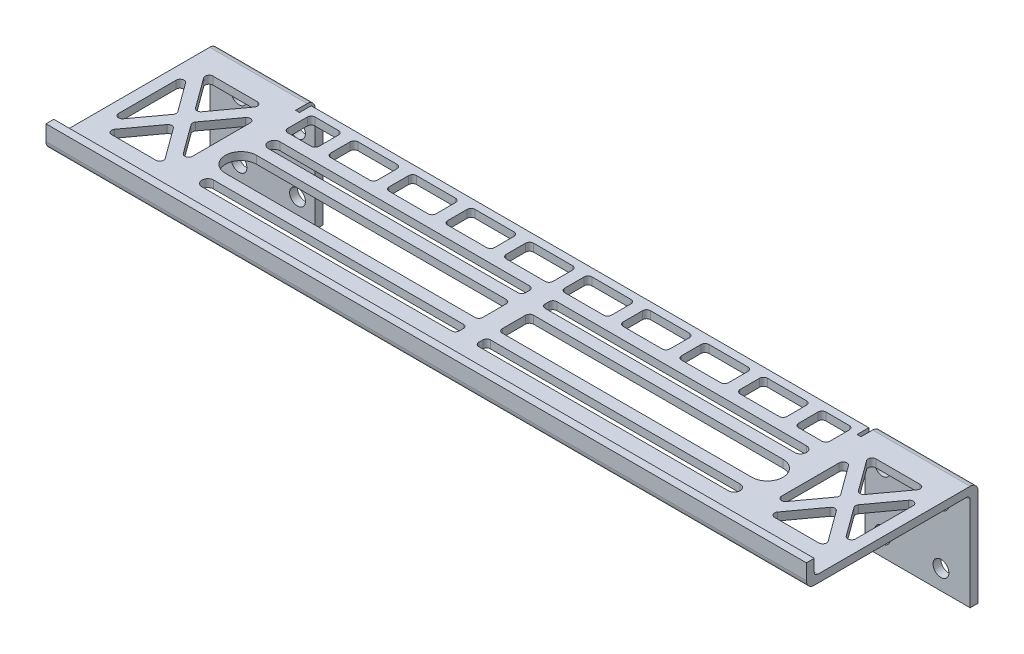
SolidWorks part; units mm, degrees
material "AISI 304"
ref_plane "Front Plane" through (0, 0, 0) normal (0, 0, 1) x (1, 0, 0)
ref_plane "Top Plane" through (0, 0, 0) normal (0, 1, 0) x (1, 0, 0)
ref_plane "Right Plane" through (0, 0, 0) normal (1, 0, 0) x (0, 0, -1)
sketch "Sketch1" plane through (0, 0, 0) normal (0, 1, 0) x (1, 0, 0)
  line L1 (-97.5, 17.5) -> (97.5, 17.5)
  line L2 (-97.5, 17.5) -> (-97.5, -17.5)
  line L3 (-97.5, -17.5) -> (97.5, -17.5)
  line L4 (97.5, 17.5) -> (97.5, -17.5)
  line L5 (-97.5, 17.5) -> (97.5, -17.5) construction
  line L6 (-97.5, -17.5) -> (97.5, 17.5) construction
  point P0 (0, 0)
  dimension "D1" = 195
  dimension "D2" = 35
extrude "Boss-Extrude1" add sketch "Sketch1" along normal blind 2
sketch "Sketch2" plane through (0, 0, -17.5) normal (0, 0, -1) x (-1, 0, 0)
  line L0 (-97.5, 2) -> (-97.5, -25)
  line L1 (-97.5, -25) -> (-72.5, -25)
  line L2 (-72.5, -25) -> (-72.5, 2)
  line L3 (-97.5, 2) -> (97.5, 2) construction
  line L4 (-72.5, 2) -> (-97.5, 2)
  line L5 (0, 22.3225) -> (0, -25) construction
  line L6 (72.5, -25) -> (72.5, 2)
  line L7 (97.5, -25) -> (72.5, -25)
  line L8 (97.5, 2) -> (97.5, -25)
  line L9 (72.5, 2) -> (97.5, 2)
  dimension "D1" = 25
  dimension "D2" = 27
extrude "Boss-Extrude2" add sketch "Sketch2" along normal blind 2
fillet "Fillet1" radius 2 2 edges at (-85, 2, -19.5) (85, 2, -19.5)
fillet "Fillet2" radius 1 2 edges at (85, 0, -17.5) (-85, 0, -17.5)
sketch "Sketch3" plane through (0, 2, 0) normal (0, 1, 0) x (1, 0, 0)
  line L0 (-72.5, 17.5) -> (-72.5, 14.5)
  line L1 (-72.5, 14.5) -> (-71.5, 14.5)
  line L2 (-71.5, 14.5) -> (-71.5, 17.5)
  line L3 (72.5, 17.5) -> (-72.5, 17.5) construction
  line L4 (-71.5, 17.5) -> (-72.5, 17.5)
  line L5 (0, 27.242) -> (0, -22.4777) construction
  line L6 (71.5, 14.5) -> (71.5, 17.5)
  line L7 (72.5, 14.5) -> (71.5, 14.5)
  line L8 (72.5, 17.5) -> (72.5, 14.5)
  line L9 (71.5, 17.5) -> (72.5, 17.5)
  dimension "D1" = 1
  dimension "D2" = 3
extrude "Cut-Extrude1" cut sketch "Sketch3" against normal through all
sketch "Sketch4" plane through (0, 2, 0) normal (0, 1, 0) x (1, 0, 0)
  line L1 (-97.5, 17.5) -> (-97.5, -17.5) construction
  line L2 (97.5, -17.5) -> (97.5, 17.5) construction
  line L3 (-67.5, -4.5) -> (67.5, -4.5) construction
  line L4 (-67.5, -0.5) -> (67.5, -0.5)
  line L5 (-67.5, -8.5) -> (67.5, -8.5)
  line L6 (-97.5, -13) -> (97.5, -13) construction
  line L7 (-97.5, 4) -> (97.5, 4) construction
  line L8 (-67.5, 4) -> (67.5, 4) construction
  line L9 (-67.5, 5.5025) -> (67.5, 5.5025)
  line L10 (-67.5, 2.4975) -> (67.5, 2.4975)
  line L11 (67.5, -4.5) -> (67.5, 13.2752) construction
  line L12 (-67.5, -4.5) -> (-67.5, 15.5373) construction
  line L13 (-67.5, -13) -> (67.5, -13) construction
  line L14 (-67.5, -14.5025) -> (67.5, -14.5025)
  line L15 (-67.5, -11.4975) -> (67.5, -11.4975)
  line L16 (71.5, 17.5) -> (-71.5, 17.5) construction
  line L17 (67.5, -4.5) -> (67.5, -23.9923) construction
  line L18 (-67.5, -4.5) -> (-67.5, -26.609) construction
  arc A0 (-67.5, -0.5) -> (-67.5, -8.5) centre (-67.5, -4.5) ccw
  arc A1 (67.5, -8.5) -> (67.5, -0.5) centre (67.5, -4.5) ccw
  arc A2 (-67.5, 5.5025) -> (-67.5, 2.4975) centre (-67.5, 4) ccw
  arc A3 (67.5, 2.4975) -> (67.5, 5.5025) centre (67.5, 4) ccw
  arc A4 (-67.5, -14.5025) -> (-67.5, -11.4975) centre (-67.5, -13) cw
  arc A5 (67.5, -11.4975) -> (67.5, -14.5025) centre (67.5, -13) cw
  point P8 (0, -4.5)
  point P19 (0, 4)
  point P26 (-67.5, -10)
  point P31 (0, -13)
  dimension "D1" = 4
  dimension "D6" = 1.5025
  dimension "D8" = 1.5025
  dimension "D2" = 30
  dimension "D3" = 30
  dimension "D5" = 8.5
  dimension "D4" = 8.5
  dimension "D7" = 22
extrude "Cut-Extrude2" cut sketch "Sketch4" against normal through all
sketch "Sketch6" plane through (0, 2, 0) normal (0, 1, 0) x (1, 0, 0)
  line L0 (0, 24.7593) -> (0, -32.236) construction
  line L1 (-75.5, 8.9577) -> (-75.5, -11.9577)
  line L2 (-72.5, 14.5) -> (-97.5, 14.5) construction
  line L3 (-72.5, 14.5) -> (-72.5, -17.5) construction
  line L4 (-72.5, -17.5) -> (-97.5, -17.5) construction
  line L5 (-97.5, 14.5) -> (-97.5, -17.5) construction
  line L6 (-77.3578, -14.5) -> (-92.6422, -14.5)
  line L7 (-94.5, 8.9577) -> (-94.5, -11.9577)
  line L8 (-77.3578, 11.5) -> (-92.6422, 11.5)
  line L9 (-94.5, 11.5) -> (-75.5, -14.5) construction
  line L10 (-75.5, 11.5) -> (-94.5, -14.5) construction
  line L11 (-94.5, 8.9577) -> (-86.8578, -1.5)
  line L12 (-77.3578, 11.5) -> (-85, 1.0423)
  line L13 (-92.6422, 11.5) -> (-85, 1.0423)
  line L14 (-75.5, 8.9577) -> (-83.1422, -1.5)
  line L15 (-86.8578, -1.5) -> (-94.5, -11.9577)
  line L16 (-93.2889, 12.385) -> (-74.2889, -13.615) construction
  line L17 (-95.7111, 10.615) -> (-76.7111, -15.385) construction
  line L18 (-76.7111, 12.385) -> (-95.7111, -13.615) construction
  line L19 (-74.2889, 10.615) -> (-93.2889, -15.385) construction
  line L20 (-94.5, 11.5) -> (-94.5, -14.5) construction
  line L21 (-75.5, 11.5) -> (-94.5, 11.5) construction
  line L22 (-75.5, 11.5) -> (-75.5, -14.5) construction
  line L23 (-75.5, -14.5) -> (-94.5, -14.5) construction
  line L24 (-85, -4.0423) -> (-77.3578, -14.5)
  line L25 (-85, -4.0423) -> (-92.6422, -14.5)
  line L26 (-83.1422, -1.5) -> (-75.5, -11.9577)
  line L27 (75.5, 11.5) -> (94.5, -14.5) construction
  line L28 (94.5, 11.5) -> (75.5, -14.5) construction
  line L29 (97.5, 14.5) -> (97.5, -17.5) construction
  line L30 (72.5, -17.5) -> (97.5, -17.5) construction
  line L31 (72.5, 14.5) -> (72.5, -17.5) construction
  line L32 (72.5, 14.5) -> (97.5, 14.5) construction
  line L33 (83.1422, -1.5) -> (75.5, -11.9577)
  line L34 (85, -4.0423) -> (92.6422, -14.5)
  line L35 (85, -4.0423) -> (77.3578, -14.5)
  line L36 (86.8578, -1.5) -> (94.5, -11.9577)
  line L37 (75.5, 8.9577) -> (83.1422, -1.5)
  line L38 (92.6422, 11.5) -> (85, 1.0423)
  line L39 (77.3578, 11.5) -> (85, 1.0423)
  line L40 (94.5, 8.9577) -> (86.8578, -1.5)
  line L41 (77.3578, 11.5) -> (92.6422, 11.5)
  line L42 (94.5, 8.9577) -> (94.5, -11.9577)
  line L43 (77.3578, -14.5) -> (92.6422, -14.5)
  line L44 (75.5, 8.9577) -> (75.5, -11.9577)
  dimension "D1" = 3
  dimension "D2" = 1.5
  dimension "D3" = 1.5
extrude "Cut-Extrude4" cut sketch "Sketch6" against normal through all
fillet "Fillet3" radius 1 24 edges at (92.6422, 1, 14.5) (77.3578, 1, 14.5) (75.5, 1, 11.9577) (94.5, 1, 11.9577) (85, 1, 4.0423) (75.5, 1, -8.9577) (94.5, 1, -8.9577) (92.6422, 1, -11.5) (77.3578, 1, -11.5) (86.8578, 1, 1.5) (83.1422, 1, 1.5) (85, 1, -1.0423) (-92.6422, 1, -11.5) (-85, 1, -1.0423) (-77.3578, 1, -11.5) (-75.5, 1, -8.9577) (-75.5, 1, 11.9577) (-77.3578, 1, 14.5) (-85, 1, 4.0423) (-83.1422, 1, 1.5) (-92.6422, 1, 14.5) (-94.5, 1, 11.9577) (-86.8578, 1, 1.5) (-94.5, 1, -8.9577)
sketch "Sketch7" plane through (0, 0, -19.5) normal (0, 0, -1) x (-1, 0, 0)
  line L0 (0, 25.9328) -> (0, -38.6438) construction
  line L1 (-97.5, -12.5) -> (97.5, -12.5) construction
  line L2 (-97.5, 0) -> (-97.5, -25) construction
  line L3 (97.5, -25) -> (97.5, 0) construction
  line L4 (-97.5, -20) -> (97.5, -20) construction
  line L5 (-97.5, -5) -> (97.5, -5) construction
  circle A0 centre (-90, -5) radius 2.025
  circle A1 centre (-75, -5) radius 2.025
  circle A2 centre (-75, -20) radius 2.025
  circle A3 centre (-90, -20) radius 2.025
  circle A4 centre (90, -20) radius 2.025
  circle A5 centre (75, -20) radius 2.025
  circle A6 centre (75, -5) radius 2.025
  circle A7 centre (90, -5) radius 2.025
  dimension "D3" = 4.05
  dimension "D4" = 90
  dimension "D7" = 15
  dimension "D8" = 15
  dimension "D1" = 7.5
  dimension "D2" = 7.5
  dimension "D5" = 2
  dimension "D6" = 2
extrude "Cut-Extrude5" cut sketch "Sketch7" against normal through all
sketch "Sketch8" plane through (0, 0, -19.5) normal (0, 0, -1) x (-1, 0, 0)
  line L0 (-72.5, -2) -> (-70.5, -2)
  line L1 (-72.5, -25) -> (-72.5, 0) construction
  line L2 (-70.5, -2) -> (-70.5, -25)
  line L3 (-70.5, -25) -> (-72.5, -25)
  line L4 (-72.5, -25) -> (-72.5, -2)
  line L5 (-97.5, -25) -> (-72.5, -25) construction
  line L6 (-71.5, 0) -> (71.5, 0) construction
  line L7 (0, 16.8942) -> (0, -14.9488) construction
  line L8 (70.5, -25) -> (72.5, -25)
  line L9 (70.5, -2) -> (70.5, -25)
  line L10 (72.5, -2) -> (70.5, -2)
  line L11 (72.5, -25) -> (72.5, -2)
  dimension "D1" = 2
  dimension "D2" = 2
extrude "Boss-Extrude3" add sketch "Sketch8" against normal blind 2
sketch "Sketch10" plane through (0, 2, 0) normal (0, 1, 0) x (1, 0, 0)
  line L0 (-97.5, -17.5) -> (-97.5, -22.5)
  line L1 (-97.5, -22.5) -> (97.5, -22.5)
  line L2 (97.5, -22.5) -> (97.5, -17.5)
  line L3 (97.5, -17.5) -> (-97.5, -17.5)
  dimension "D1" = 5
extrude "Boss-Extrude5" add sketch "Sketch10" against normal blind 2
sketch "Sketch11" plane through (0, 0, 22.5) normal (0, 0, 1) x (1, 0, 0)
  line L0 (97.5, 0) -> (-97.5, 0)
  line L1 (-97.5, 0) -> (-97.5, 6)
  line L2 (-97.5, 6) -> (97.5, 6)
  line L3 (97.5, 6) -> (97.5, 0)
  dimension "D1" = 6
extrude "Boss-Extrude6" add sketch "Sketch11" along normal blind 2
fillet "Fillet4" radius 1 1 edges at (0, 2, 22.5)
fillet "Fillet5" radius 2 1 edges at (0, 0, 24.5)
sketch "Sketch13" plane through (0, 2, 0) normal (0, 1, 0) x (1, 0, 0)
  line L0 (71.5, 14.5) -> (71.5, 4.7495) construction
  line L1 (67.5, 5.5025) -> (-67.5, 5.5025) construction
  line L2 (-71.5, 17.5) -> (71.5, 17.5) construction
  line L3 (-71.5, 17.5) -> (-71.5, 6.5025) construction
  line L4 (-71.5, 6.5025) -> (71.5, 6.5025) construction
  line L5 (71.5, 17.5) -> (71.5, 6.5025) construction
  line L6 (-69.5, 14.5) -> (-69.5, 9.5025)
  line L7 (-68.5, 8.5025) -> (68.5, 8.5025)
  line L8 (69.5, 14.5) -> (69.5, 9.5025)
  line L9 (-68.5, 15.5) -> (68.5, 15.5)
  line L10 (-69.5, 8.5025) -> (69.5, 8.5025) construction
  line L11 (69.5, 15.5) -> (69.5, 8.5025) construction
  line L12 (-69.5, 15.5) -> (69.5, 15.5) construction
  line L13 (-69.5, 15.5) -> (-69.5, 8.5025) construction
  arc A0 (68.5, 8.5025) -> (69.5, 9.5025) centre (68.5, 9.5025) ccw
  arc A1 (69.5, 14.5) -> (68.5, 15.5) centre (68.5, 14.5) ccw
  arc A2 (-69.5, 9.5025) -> (-68.5, 8.5025) centre (-68.5, 9.5025) ccw
  arc A3 (-69.5, 14.5) -> (-68.5, 15.5) centre (-68.5, 14.5) cw
  dimension "D3" = 1
  dimension "D1" = 1
  dimension "D2" = 2
extrude "Cut-Extrude6" cut sketch "Sketch13" against normal blind 10
sketch "Sketch14" plane through (0, 2, 0) normal (0, 1, 0) x (1, 0, 0)
  line L0 (0, 36.2866) -> (0, -44.5357) construction
  line L1 (1.5, 15.5) -> (-1.5, 15.5)
  line L2 (68.5, 15.5) -> (-68.5, 15.5) construction
  line L3 (-1.5, 15.5) -> (-1.5, 8.5025)
  line L4 (-68.5, 8.5025) -> (68.5, 8.5025) construction
  line L5 (-1.5, 8.5025) -> (1.5, 8.5025)
  line L6 (1.5, 15.5) -> (1.5, 8.5025)
  line L7 (13.5, 8.5025) -> (16.5, 8.5025)
  line L8 (16.5, 15.5) -> (16.5, 8.5025)
  line L9 (16.5, 15.5) -> (13.5, 15.5)
  line L10 (13.5, 15.5) -> (13.5, 8.5025)
  line L11 (28.5, 8.5025) -> (31.5, 8.5025)
  line L12 (31.5, 15.5) -> (31.5, 8.5025)
  line L13 (31.5, 15.5) -> (28.5, 15.5)
  line L14 (28.5, 15.5) -> (28.5, 8.5025)
  line L15 (43.5, 8.5025) -> (46.5, 8.5025)
  line L16 (46.5, 15.5) -> (46.5, 8.5025)
  line L17 (46.5, 15.5) -> (43.5, 15.5)
  line L18 (43.5, 15.5) -> (43.5, 8.5025)
  line L19 (58.5, 8.5025) -> (61.5, 8.5025)
  line L20 (61.5, 15.5) -> (61.5, 8.5025)
  line L21 (61.5, 15.5) -> (58.5, 15.5)
  line L22 (58.5, 15.5) -> (58.5, 8.5025)
  line L23 (-16.5, 8.5025) -> (-13.5, 8.5025)
  line L24 (-13.5, 15.5) -> (-13.5, 8.5025)
  line L25 (-13.5, 15.5) -> (-16.5, 15.5)
  line L26 (-16.5, 15.5) -> (-16.5, 8.5025)
  line L27 (-31.5, 8.5025) -> (-28.5, 8.5025)
  line L28 (-28.5, 15.5) -> (-28.5, 8.5025)
  line L29 (-28.5, 15.5) -> (-31.5, 15.5)
  line L30 (-31.5, 15.5) -> (-31.5, 8.5025)
  line L31 (-46.5, 8.5025) -> (-43.5, 8.5025)
  line L32 (-43.5, 15.5) -> (-43.5, 8.5025)
  line L33 (-43.5, 15.5) -> (-46.5, 15.5)
  line L34 (-46.5, 15.5) -> (-46.5, 8.5025)
  line L35 (-61.5, 8.5025) -> (-58.5, 8.5025)
  line L36 (-58.5, 15.5) -> (-58.5, 8.5025)
  line L37 (-58.5, 15.5) -> (-61.5, 15.5)
  line L38 (-61.5, 15.5) -> (-61.5, 8.5025)
  point P12 (0, 8.5025)
  point P13 (0, 15.5)
  dimension "D1" = 1.5
  dimension "D3" = 61.5
  dimension "D5" = 61.5
  dimension "D2" = 5
  dimension "D4" = 5
extrude "Boss-Extrude8" add sketch "Sketch14" against normal blind 2
fillet "Fillet8" radius 1 36 edges at (-61.5, 1, -15.5) (-46.5, 1, -15.5) (-31.5, 1, -15.5) (-16.5, 1, -15.5) (-1.5, 1, -15.5) (13.5, 1, -15.5) (28.5, 1, -15.5) (43.5, 1, -15.5) (58.5, 1, -15.5) (58.5, 1, -8.5025) (43.5, 1, -8.5025) (28.5, 1, -8.5025) (13.5, 1, -8.5025) (-1.5, 1, -8.5025) (-16.5, 1, -8.5025) (-31.5, 1, -8.5025) (-46.5, 1, -8.5025) (-61.5, 1, -8.5025) (-58.5, 1, -8.5025) (-43.5, 1, -8.5025) (-28.5, 1, -8.5025) (-13.5, 1, -8.5025) (1.5, 1, -8.5025) (16.5, 1, -8.5025) (31.5, 1, -8.5025) (46.5, 1, -8.5025) (-13.5, 1, -15.5) (-28.5, 1, -15.5) (-43.5, 1, -15.5) (-58.5, 1, -15.5) (1.5, 1, -15.5) (16.5, 1, -15.5) (31.5, 1, -15.5) (46.5, 1, -15.5) (61.5, 1, -15.5) (61.5, 1, -8.5025)
sketch "Sketch15" plane through (0, 2, 0) normal (0, 1, 0) x (1, 0, 0)
  line L0 (0, 28.4345) -> (0, -49.6802) construction
  line L1 (2.5, 5.5025) -> (-2.5, 5.5025)
  line L2 (67.5, 5.5025) -> (-67.5, 5.5025) construction
  line L3 (-2.5, 5.5025) -> (-2.5, -14.5025)
  line L4 (-67.5, -14.5025) -> (67.5, -14.5025) construction
  line L5 (-2.5, -14.5025) -> (2.5, -14.5025)
  line L6 (2.5, 5.5025) -> (2.5, -14.5025)
  point P7 (0, 5.5025)
  point P13 (0, -14.5025)
  point P14 (0, 5.5025)
  dimension "D1" = 2.5
extrude "Boss-Extrude9" add sketch "Sketch15" against normal blind 2
fillet "Fillet9" radius 1 12 edges at (-2.5, 1, -2.4975) (-2.5, 1, 8.5) (-2.5, 1, 14.5025) (-2.5, 1, 11.4975) (-2.5, 1, 0.5) (-2.5, 1, -5.5025) (2.5, 1, 11.4975) (2.5, 1, 0.5) (2.5, 1, -5.5025) (2.5, 1, -2.4975) (2.5, 1, 8.5) (2.5, 1, 14.5025)
